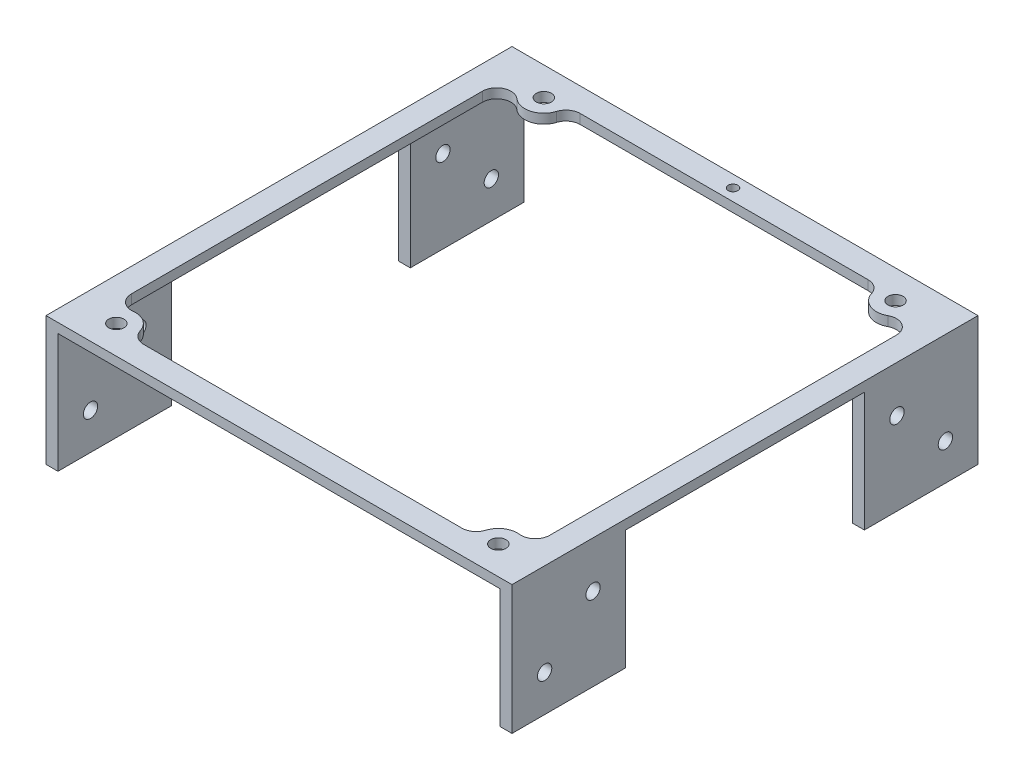
SolidWorks part; units mm, degrees
ref_plane "Front" through (0, 0, 0) normal (0, 0, 1) x (1, 0, 0)
ref_plane "Top" through (0, 0, 0) normal (0, 1, 0) x (1, 0, 0)
ref_plane "Right" through (0, 0, 0) normal (1, 0, 0) x (0, 0, -1)
sketch "Эскиз1" plane through (0, 0, 0) normal (0, 1, 0) x (1, 0, 0)
  line L0 (0, 0) -> (97.6, 97.6) construction
  line L1 (0, 0) -> (97.6, 0)
  line L2 (0, 0) -> (0, 97.6)
  line L3 (0, 97.6) -> (97.6, 97.6)
  line L4 (97.6, 0) -> (97.6, 97.6)
  line L5 (97.6, 0) -> (0, 97.6) construction
  line L25 (79.5765, 92.6) -> (19.2935, 92.6)
  line L27 (92.6, 85.5105) -> (92.6, 12.8897)
  line L29 (5, 86.393) -> (5, 12.8897)
  line L33 (82.1165, 5) -> (15.4835, 5)
  circle A0 centre (86.265, 91.665) radius 1.59
  circle A1 centre (88.805, 5.935) radius 1.59
  circle A2 centre (8.795, 5.935) radius 1.59
  circle A3 centre (12.605, 91.665) radius 1.59
  arc A29 (9.9736, 88.6524) -> (16.427, 90.485) centre (12.605, 91.665) ccw
  arc A30 (82.443, 90.485) -> (88.1707, 88.1481) centre (86.265, 91.665) ccw
  arc A31 (89.2593, 9.9091) -> (84.983, 7.115) centre (88.805, 5.935) ccw
  arc A32 (12.617, 7.115) -> (8.3407, 9.9091) centre (8.795, 5.935) ccw
  arc A33 (92.6, 12.8897) -> (89.2593, 9.9091) centre (89.6, 12.8897) cw
  arc A34 (82.1165, 5) -> (84.983, 7.115) centre (82.1165, 8) ccw
  arc A35 (15.4835, 5) -> (12.617, 7.115) centre (15.4835, 8) cw
  arc A36 (5, 12.8897) -> (8.3407, 9.9091) centre (8, 12.8897) ccw
  arc A37 (9.9736, 88.6524) -> (5, 86.393) centre (8, 86.393) ccw
  arc A38 (88.1707, 88.1481) -> (92.6, 85.5105) centre (89.6, 85.5105) cw
  arc A39 (19.2935, 92.6) -> (16.427, 90.485) centre (19.2935, 89.6) ccw
  arc A40 (82.443, 90.485) -> (79.5765, 92.6) centre (79.5765, 89.6) ccw
  point P19 (48.8, 48.8)
  dimension "D1" = 3
  dimension "D2" = 3
  dimension "D3" = 3
  dimension "D4" = 3
  dimension "D5" = 3
  dimension "D6" = 3
extrude "Бобышка-Вытянуть1" add sketch "Эскиз1" along normal blind 2
sketch "Эскиз2" plane through (0, 2, 0) normal (0, 1, 0) x (1, 0, 0)
  line L0 (48.8, 97.6) -> (48.8, 92.6) construction
  line L1 (97.6, 97.6) -> (0, 97.6) construction
  line L2 (79.5765, 92.6) -> (19.2935, 92.6) construction
  circle A0 centre (48.8, 95.1) radius 1
extrude "Вырез-Вытянуть1" cut sketch "Эскиз2" against normal through all
sketch "Эскиз7" plane through (0, 2, 0) normal (0, 1, 0) x (1, 0, 0)
  line L0 (3.715, 37.25) -> (3.715, 2.855) construction
  line L1 (5.7156, 0.8544) -> (37.2506, 0.8544) construction
  line L2 (39.6506, 3.2544) -> (57.9506, 3.2544) construction
  line L3 (60.3506, 0.8544) -> (91.8856, 0.8544) construction
  line L4 (93.885, 2.8538) -> (93.885, 37.25) construction
  line L5 (91.485, 39.65) -> (91.485, 57.95) construction
  line L6 (93.885, 60.35) -> (93.885, 94.745) construction
  line L7 (91.885, 96.745) -> (60.35, 96.745) construction
  line L8 (57.95, 94.345) -> (39.65, 94.345) construction
  line L9 (37.25, 96.745) -> (5.715, 96.745) construction
  line L10 (3.715, 94.745) -> (3.715, 60.35) construction
  line L11 (6.115, 57.95) -> (6.115, 39.65) construction
  line L12 (6.115, 48.8) -> (91.485, 48.8) construction
  line L13 (48.8006, 3.2544) -> (48.8, 94.345) construction
  line L15 (0, 0) -> (2.5, 0)
  line L16 (0, 0) -> (0, 23.8)
  line L17 (0, 23.8) -> (2.5, 23.8)
  line L18 (2.5, 0) -> (2.5, 23.8)
  line L27 (0, 97.6) -> (2.5, 97.6)
  line L28 (0, 97.6) -> (0, 73.8)
  line L29 (0, 73.8) -> (2.5, 73.8)
  line L30 (2.5, 97.6) -> (2.5, 73.8)
  line L32 (97.6, 97.6) -> (95.1, 97.6)
  line L33 (97.6, 97.6) -> (97.6, 73.8)
  line L34 (97.6, 73.8) -> (95.1, 73.8)
  line L35 (95.1, 97.6) -> (95.1, 73.8)
  line L36 (97.6, 0) -> (95.1, 0)
  line L37 (97.6, 0) -> (97.6, 23.8)
  line L38 (97.6, 23.8) -> (95.1, 23.8)
  line L39 (95.1, 0) -> (95.1, 23.8)
  arc A4 (3.715, 94.745) -> (5.715, 96.745) centre (5.715, 94.745) cw construction
  arc A5 (38.45, 95.545) -> (37.25, 96.745) centre (37.25, 95.545) ccw construction
  arc A6 (38.45, 95.545) -> (39.65, 94.345) centre (39.65, 95.545) ccw construction
  arc A7 (59.15, 95.545) -> (57.95, 94.345) centre (57.95, 95.545) cw construction
  arc A8 (59.15, 95.545) -> (60.35, 96.745) centre (60.35, 95.545) cw construction
  arc A9 (59.1506, 2.0544) -> (60.3506, 0.8544) centre (60.3506, 2.0544) ccw construction
  arc A10 (59.1506, 2.0544) -> (57.9506, 3.2544) centre (57.9506, 2.0544) ccw construction
  arc A11 (38.4506, 2.0544) -> (39.6506, 3.2544) centre (39.6506, 2.0544) cw construction
  arc A12 (38.4506, 2.0544) -> (37.2506, 0.8544) centre (37.2506, 2.0544) cw construction
  arc A13 (3.715, 60.35) -> (4.915, 59.15) centre (4.915, 60.35) ccw construction
  arc A14 (6.115, 57.95) -> (4.915, 59.15) centre (4.915, 57.95) ccw construction
  arc A15 (6.115, 39.65) -> (4.915, 38.45) centre (4.915, 39.65) cw construction
  arc A16 (3.715, 37.25) -> (4.915, 38.45) centre (4.915, 37.25) cw construction
  arc A17 (93.885, 37.25) -> (92.685, 38.45) centre (92.685, 37.25) ccw construction
  arc A18 (91.485, 39.65) -> (92.685, 38.45) centre (92.685, 39.65) ccw construction
  arc A19 (91.485, 57.95) -> (92.685, 59.15) centre (92.685, 57.95) cw construction
  arc A20 (93.885, 60.35) -> (92.685, 59.15) centre (92.685, 60.35) cw construction
  arc A21 (91.885, 96.745) -> (93.885, 94.745) centre (91.885, 94.745) cw construction
  arc A22 (3.715, 2.855) -> (5.7156, 0.8544) centre (5.7156, 2.855) ccw construction
  arc A23 (91.8856, 0.8544) -> (93.885, 2.8538) centre (91.8856, 2.8538) ccw construction
extrude "Бобышка-Вытянуть2" add sketch "Эскиз7" against normal blind 25 from surface at -2 starting at face at (48.8, 0, -94.1)
sketch "Эскиз8" plane through (0, 0, 0) normal (-1, 0, 0) x (0, 0, 1)
  line L0 (-73.8, 0) -> (-97.6, 0) construction
  line L1 (-97.6, 2) -> (-97.6, -25) construction
  line L2 (-97.6, 0) -> (-73.8, -25) construction
  line L3 (-85.7, -12.5) -> (-80.6301, -7.6734) construction
  line L4 (-48.8, 0) -> (-48.8, -25) construction
  line L5 (-73.8, 0) -> (-23.8, 0) construction
  circle A0 centre (-80.6301, -7.6734) radius 1.5
  circle A1 centre (-90.7699, -17.3266) radius 1.5
  circle A2 centre (-6.8301, -17.3266) radius 1.5
  circle A3 centre (-16.9699, -7.6734) radius 1.5
  point P17 (0, 0)
extrude "Вырез-Вытянуть2" cut sketch "Эскиз8" against normal through all
